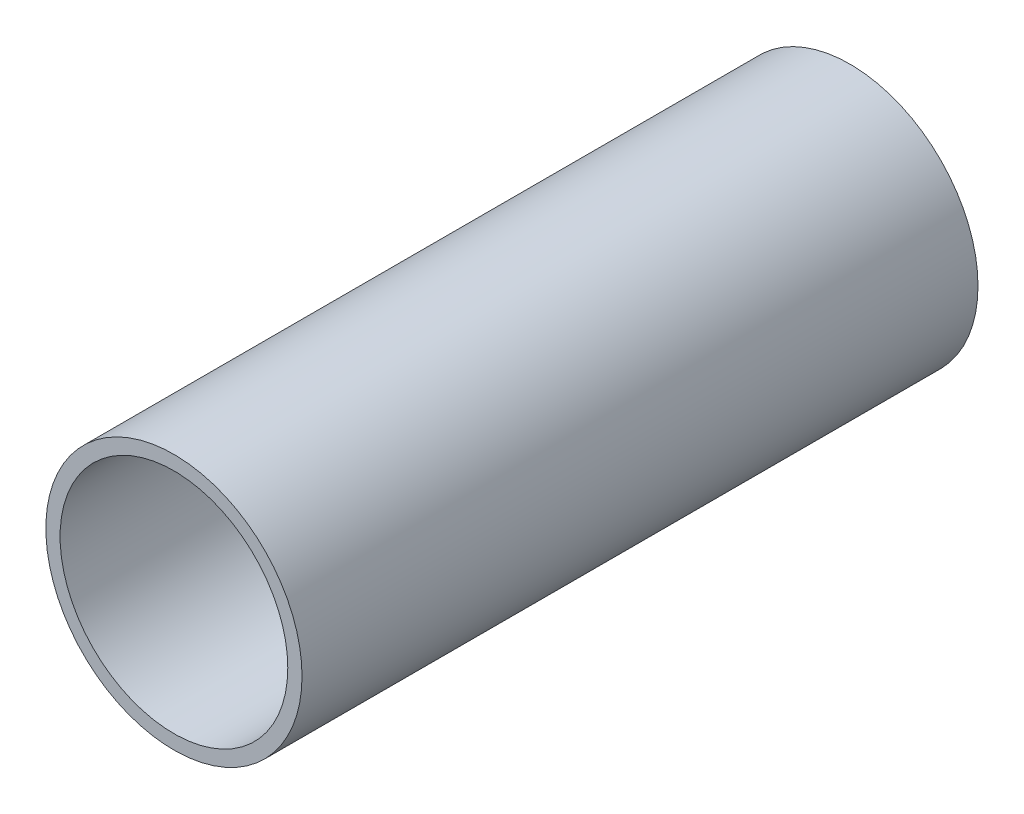
SolidWorks part; units mm, degrees
ref_plane "Front Plane" through (0, 0, 0) normal (0, 0, 1) x (1, 0, 0)
ref_plane "Top Plane" through (0, 0, 0) normal (0, 1, 0) x (1, 0, 0)
ref_plane "Right Plane" through (0, 0, 0) normal (1, 0, 0) x (0, 0, -1)
sketch "Sketch1" plane through (0, 0, 0) normal (0, 0, 1) x (1, 0, 0)
  circle A0 centre (0, 0) radius 57.15
  dimension "D1" = 114.3
extrude "Boss-Extrude1" add sketch "Sketch1" along normal mid plane 301.625 contours A0
sketch "Sketch2" plane through (0, 0, 150.8125) normal (0, 0, 1) x (1, 0, 0)
  circle A0 centre (0, 0) radius 50.8
  dimension "D1" = 101.6
extrude "Cut-Extrude1" cut sketch "Sketch2" against normal through all
